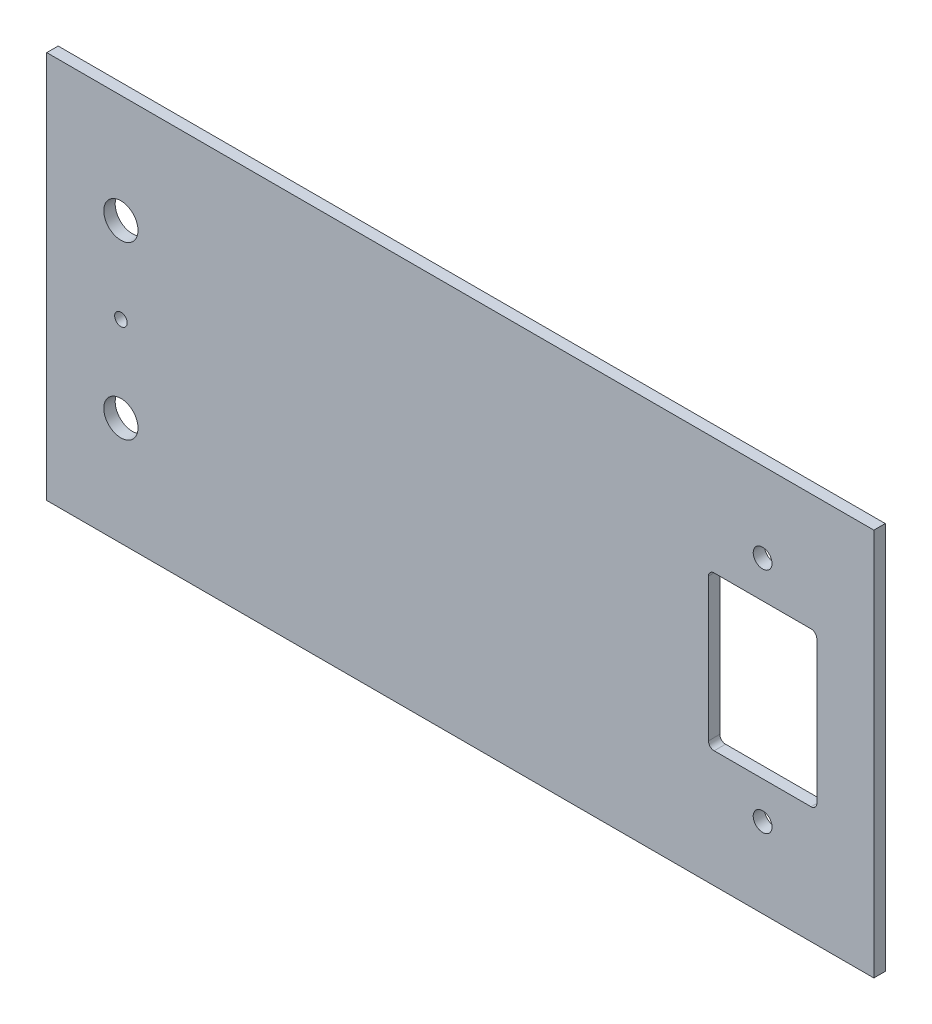
SolidWorks part; units mm, degrees
ref_plane "Front Plane" through (0, 0, 0) normal (0, 0, 1) x (1, 0, 0)
ref_plane "Top Plane" through (0, 0, 0) normal (0, 1, 0) x (1, 0, 0)
ref_plane "Right Plane" through (0, 0, 0) normal (1, 0, 0) x (0, 0, -1)
sketch "Sketch1" plane through (0, 0, 0) normal (0, 0, 1) x (1, 0, 0)
  line L1 (72.5, -34) -> (-72.5, -34)
  line L2 (72.5, -34) -> (72.5, 34)
  line L3 (72.5, 34) -> (-72.5, 34)
  line L4 (-72.5, -34) -> (-72.5, 34)
  line L5 (72.5, -34) -> (-72.5, 34) construction
  line L6 (72.5, 34) -> (-72.5, -34) construction
  point P0 (0, 0)
  dimension "D1" = 145
  dimension "D2" = 68
extrude "Boss-Extrude1" add sketch "Sketch1" along normal blind 2
sketch "Sketch2" plane through (0, 0, 2) normal (0, 0, 1) x (1, 0, 0)
  line L0 (-237.2112, 0) -> (92.2112, 0) construction
  line L1 (62.5, -1006.3577) -> (62.5, 48993.6423) construction
  line L2 (72.5, -34) -> (72.5, 34) construction
  line L3 (-59.5, -996.0452) -> (-59.5, 49003.9548) construction
  line L4 (-72.5, 34) -> (-72.5, -34) construction
  line L5 (53, 74.21) -> (53, -47.21) construction
  line L6 (61.5, -13.5) -> (44.5, -13.5)
  line L7 (62.5, -12.5) -> (62.5, 12.5)
  line L8 (61.5, 13.5) -> (44.5, 13.5)
  line L9 (43.5, -12.5) -> (43.5, 12.5)
  arc A0 (44.5, -13.5) -> (43.5, -12.5) centre (44.5, -12.5) cw
  arc A1 (61.5, -13.5) -> (62.5, -12.5) centre (61.5, -12.5) ccw
  arc A2 (62.5, 12.5) -> (61.5, 13.5) centre (61.5, 12.5) ccw
  arc A3 (44.5, 13.5) -> (43.5, 12.5) centre (44.5, 12.5) ccw
  circle A4 centre (53, 20) radius 1.65
  circle A5 centre (53, -20) radius 1.65
  circle A6 centre (-59.5, 15) radius 3
  circle A7 centre (-59.5, -15) radius 3
  circle A8 centre (-59.5, 0) radius 1.1
  point P3 (-72.5, 0)
  point P19 (62.5, -13.5)
  point P22 (62.5, 13.5)
  point P25 (43.5, 13.5)
  point P29 (53, 13.5)
  dimension "D5" = 1
  dimension "D6" = 40
  dimension "D7" = 3.3
  dimension "D8" = 6
  dimension "D10" = 2.2
  dimension "D1" = 10
  dimension "D2" = 13
  dimension "D3" = 19
  dimension "D4" = 27
  dimension "D9" = 30
extrude "Cut-Extrude1" cut sketch "Sketch2" against normal through all
